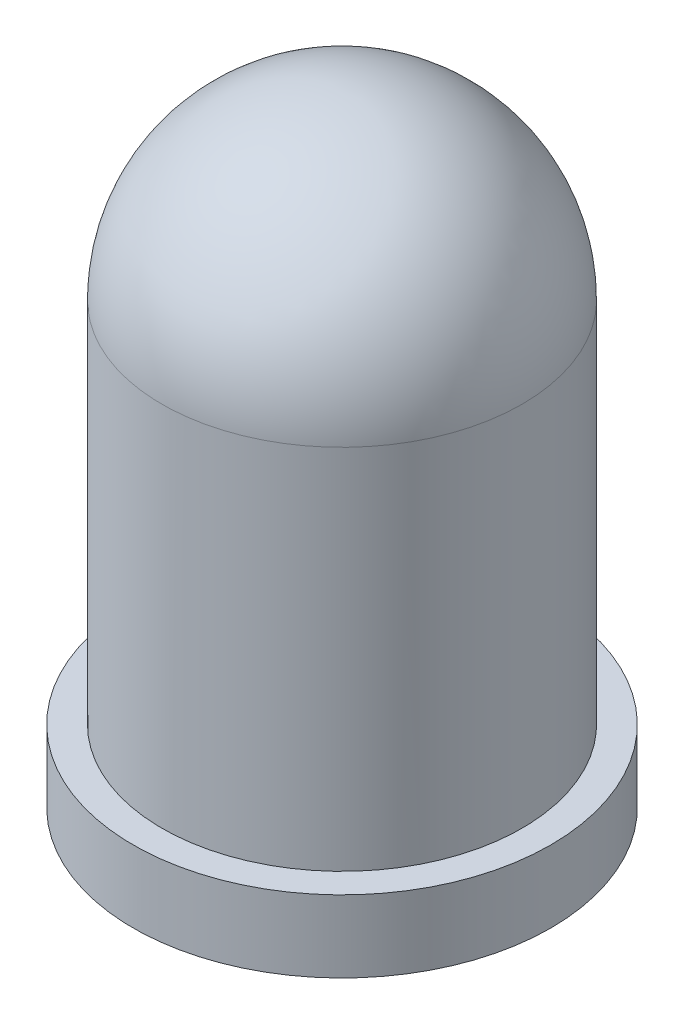
SolidWorks part; units mm, degrees
material "ABS"
ref_plane "Спереди" through (0, 0, 0) normal (0, 0, 1) x (1, 0, 0)
ref_plane "Сверху" through (0, 0, 0) normal (0, 1, 0) x (1, 0, 0)
ref_plane "Справа" through (0, 0, 0) normal (1, 0, 0) x (0, 0, -1)
sketch "Эскиз1" plane through (0, 0, 0) normal (0, 0, 1) x (1, 0, 0)
  line L0 (0, 8.6) -> (0, 0)
  line L1 (0, 0) -> (2.9, 0)
  line L2 (2.9, 0) -> (2.9, 1)
  line L3 (2.9, 1) -> (2.5, 1)
  line L4 (2.5, 1) -> (2.5, 6.1)
  arc A0 (2.5, 6.1) -> (0, 8.6) centre (0, 6.1) ccw
  dimension "D1" = 8.6
  dimension "D2" = 2.5
  dimension "D3" = 0.4
  dimension "D4" = 1
revolve "Повернуть1" add sketch "Эскиз1" angle 360 about L0
